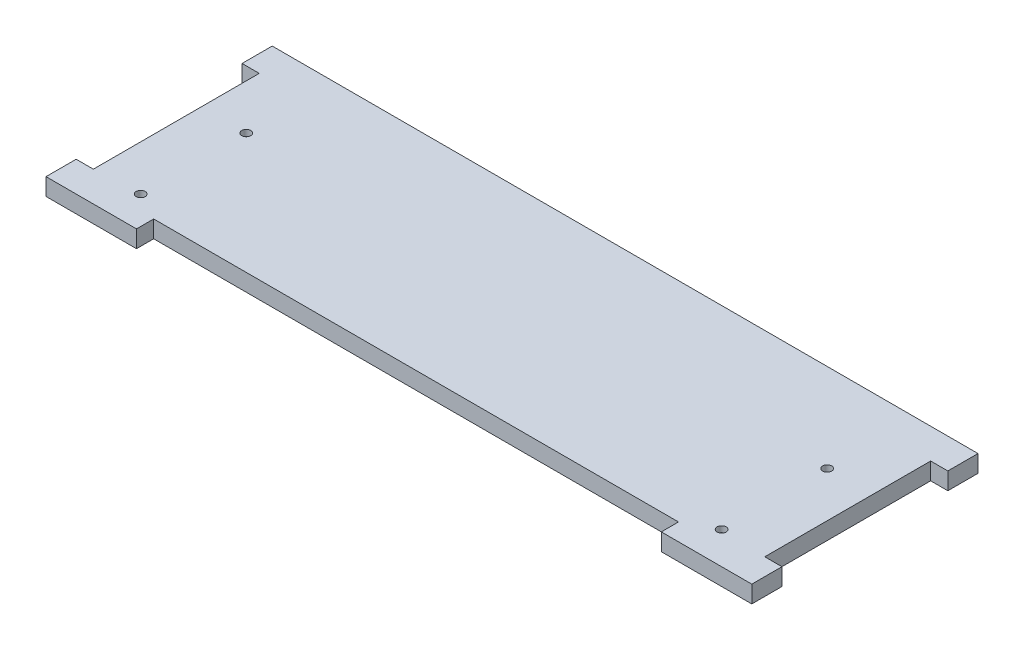
SolidWorks part; units mm, degrees
ref_plane "Front Plane" through (0, 0, 0) normal (0, 0, 1) x (1, 0, 0)
ref_plane "Top Plane" through (0, 0, 0) normal (0, 1, 0) x (1, 0, 0)
ref_plane "Right Plane" through (0, 0, 0) normal (1, 0, 0) x (0, 0, -1)
sketch "Sketch1" plane through (0, 0, 0) normal (0, 1, 0) x (1, 0, 0)
  line L1 (0, 0) -> (234, 0)
  line L2 (0, 0) -> (0, 75)
  line L3 (0, 75) -> (234, 75)
  line L4 (234, 0) -> (234, 75)
  dimension "D1" = 234
  dimension "D2" = 75
extrude "Boss-Extrude1" add sketch "Sketch1" along normal blind 5.7
sketch "Sketch2" plane through (0, 5.7, 0) normal (0, 1, 0) x (1, 0, 0)
  line L0 (0, 75) -> (0, 0) construction
  line L1 (0, 65) -> (5.7, 65)
  line L2 (0, 65) -> (0, 10)
  line L3 (0, 10) -> (5.7, 10)
  line L4 (5.7, 65) -> (5.7, 10)
  line L5 (0, 0) -> (234, 0) construction
  line L6 (234, 75) -> (0, 75) construction
  line L7 (234, 0) -> (234, 75) construction
  line L8 (234, 65) -> (228.3, 65)
  line L9 (234, 65) -> (234, 10)
  line L10 (234, 10) -> (228.3, 10)
  line L11 (228.3, 65) -> (228.3, 10)
  dimension "D1" = 10
  dimension "D2" = 10
  dimension "D3" = 5.7
  dimension "D4" = 10
  dimension "D5" = 10
  dimension "D6" = 5.7
extrude "Cut-Extrude1" cut sketch "Sketch2" against normal blind 5.7
sketch "Sketch3" plane through (0, 5.7, 0) normal (0, 1, 0) x (1, 0, 0)
  line L0 (0, 0) -> (234, 0) construction
  line L1 (30, 0) -> (204, 0)
  line L2 (30, 0) -> (30, 5.7)
  line L3 (30, 5.7) -> (204, 5.7)
  line L4 (204, 0) -> (204, 5.7)
  line L5 (0, 10) -> (0, 0) construction
  line L6 (234, 0) -> (234, 10) construction
  dimension "D1" = 30
  dimension "D2" = 30
  dimension "D3" = 5.7
extrude "Cut-Extrude2" cut sketch "Sketch3" against normal blind 5.7
sketch "Sketch4" plane through (0, 5.7, 0) normal (0, 1, 0) x (1, 0, 0)
  circle A0 centre (213.3, 45.7) radius 1.5
  circle A1 centre (213.3, 10.7) radius 1.5
  circle A2 centre (20.7, 10.7) radius 1.5
  circle A3 centre (20.7, 45.7) radius 1.5
extrude "Cut-Extrude3" cut sketch "Sketch4" against normal blind 2
